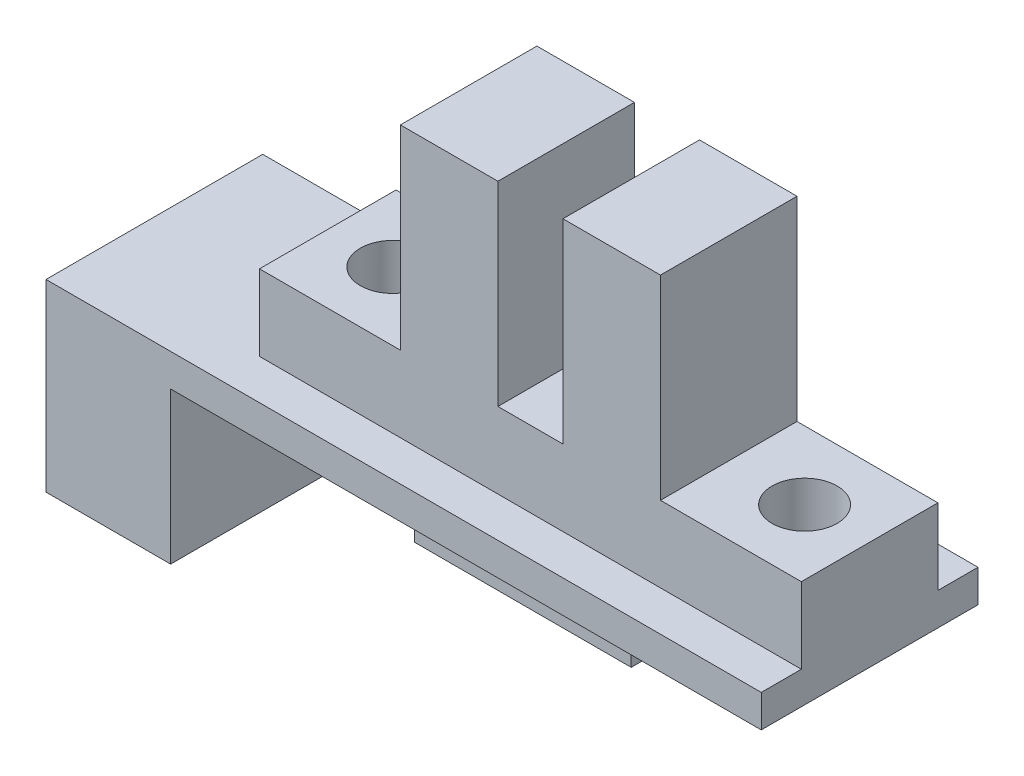
SolidWorks part; units mm, degrees
ref_plane "Спереди" through (0, 0, 0) normal (0, 0, 1) x (1, 0, 0)
ref_plane "Сверху" through (0, 0, 0) normal (0, 1, 0) x (1, 0, 0)
ref_plane "Справа" through (0, 0, 0) normal (1, 0, 0) x (0, 0, -1)
sketch "Эскиз1" plane through (0, 0, 0) normal (0, 1, 0) x (1, 0, 0)
  line L1 (16.5, 5) -> (-16.5, 5)
  line L2 (16.5, 5) -> (16.5, -5)
  line L3 (16.5, -5) -> (-16.5, -5)
  line L4 (-16.5, 5) -> (-16.5, -5)
  line L5 (16.5, 5) -> (-16.5, -5) construction
  line L6 (16.5, -5) -> (-16.5, 5) construction
  point P0 (0, 0)
  dimension "D1" = 33
  dimension "D2" = 10
extrude "Бобышка-Вытянуть1" add sketch "Эскиз1" along normal blind 1.5
sketch "Эскиз2" plane through (0, 0, 0) normal (0, -1, 0) x (1, 0, 0)
  line L0 (16.5, 0) -> (-16.5, 0) construction
  line L5 (16.5, -5) -> (-16.5, -5) construction
  line L6 (-16.5, 5) -> (-10.75, 5)
  line L7 (16.5, 5) -> (16.5, -5) construction
  line L8 (-16.5, -5) -> (-16.5, 5) construction
  line L9 (-16.5, 5) -> (-16.5, -5)
  line L10 (-16.5, -5) -> (-10.75, -5)
  line L11 (-10.75, 5) -> (-10.75, -5)
  dimension "D1" = 5.75
extrude "Бобышка-Вытянуть2" add sketch "Эскиз2" along normal blind 7
sketch "Эскиз3" plane through (0, 1.5, 0) normal (0, 1, 0) x (1, 0, 0)
  line L0 (16.5, 0) -> (-16.5, 0) construction
  line L1 (16.5, -5) -> (16.5, 5) construction
  line L2 (-16.5, 5) -> (-16.5, -5) construction
  circle A0 centre (13.5, 0) radius 1.5
  circle A1 centre (-5.5, 0) radius 1.5
  dimension "D1" = 3
  dimension "D2" = 19
  dimension "D3" = 3
extrude "Вырез-Вытянуть1" cut sketch "Эскиз3" against normal through all both and the other way through all
sketch "Эскиз4" plane through (0, 1.5, 0) normal (0, 1, 0) x (1, 0, 0)
  line L0 (-5.5, 0) -> (13.5, 0) construction
  line L2 (16.5, 3.15) -> (-8.5, 3.15)
  line L3 (16.5, 3.15) -> (16.5, -3.15)
  line L4 (16.5, -3.15) -> (-8.5, -3.15)
  line L5 (-8.5, 3.15) -> (-8.5, -3.15)
  line L6 (16.5, 3.15) -> (-8.5, -3.15) construction
  line L7 (16.5, -3.15) -> (-8.5, 3.15) construction
  circle A0 centre (13.5, 0) radius 1.5 construction
  circle A1 centre (-5.5, 0) radius 1.5 construction
  circle A2 centre (13.5, 0) radius 1.5
  circle A3 centre (-5.5, 0) radius 1.5
  point P0 (4, 0)
  dimension "D1" = 6.3
  dimension "D2" = 25
extrude "Бобышка-Вытянуть3" add sketch "Эскиз4" along normal blind 3.5
sketch "Эскиз5" plane through (0, 5, 0) normal (0, 1, 0) x (1, 0, 0)
  line L0 (-8.5, 0) -> (16.5, 0) construction
  line L1 (-8.5, 3.15) -> (-8.5, -3.15) construction
  line L2 (16.5, -3.15) -> (16.5, 3.15) construction
  line L3 (4, 3.15) -> (4, -3.15) construction
  line L4 (10, 3.15) -> (5.5, 3.15)
  line L5 (10, 3.15) -> (10, -3.15)
  line L6 (10, -3.15) -> (5.5, -3.15)
  line L7 (-2, 3.15) -> (-2, -3.15)
  line L8 (10, 3.15) -> (-2, -3.15) construction
  line L9 (10, -3.15) -> (-2, 3.15) construction
  line L10 (2.5, 3.15) -> (2.5, -3.15)
  line L11 (5.5, 3.15) -> (5.5, -3.15)
  line L12 (2.5, 3.15) -> (-2, 3.15)
  line L13 (2.5, -3.15) -> (-2, -3.15)
  point P6 (4, 0)
  dimension "D1" = 12
  dimension "D2" = 6.3
  dimension "D5" = 4.5
  dimension "D3" = 1.5
  dimension "D4" = 1.5
extrude "Бобышка-Вытянуть4" add sketch "Эскиз5" along normal blind 9
sketch "Эскиз6" plane through (0, 0, 0) normal (0, -1, 0) x (1, 0, 0)
  line L0 (-5.5, 0) -> (13.5, 0) construction
  line L2 (9, 3.5) -> (-1, 3.5)
  line L3 (9, 3.5) -> (9, -3.5)
  line L4 (9, -3.5) -> (-1, -3.5)
  line L5 (-1, 3.5) -> (-1, -3.5)
  line L6 (9, 3.5) -> (-1, -3.5) construction
  line L7 (9, -3.5) -> (-1, 3.5) construction
  point P4 (4, 0)
  dimension "D1" = 10
  dimension "D2" = 7
extrude "Бобышка-Вытянуть5" add sketch "Эскиз6" along normal blind 2
